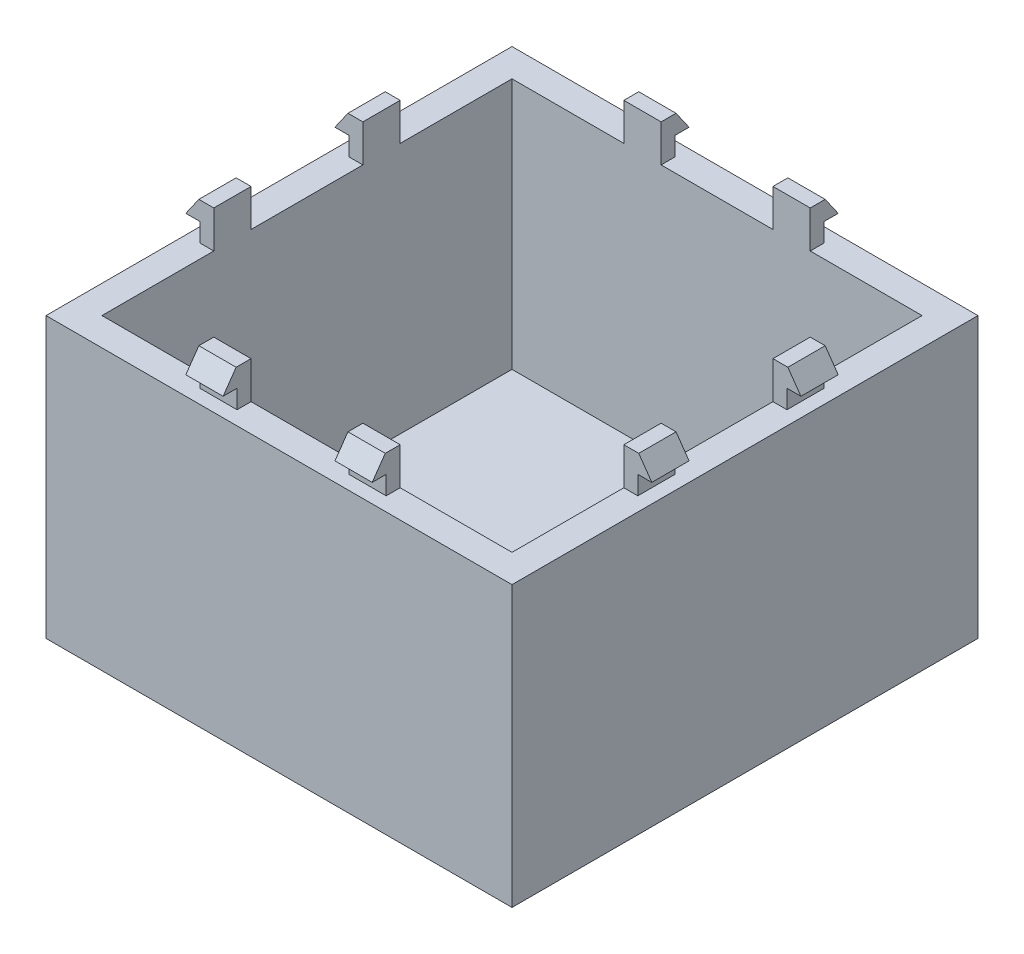
SolidWorks part; units mm, degrees
ref_plane "前视基准面" through (0, 0, 0) normal (0, 0, 1) x (1, 0, 0)
ref_plane "上视基准面" through (0, 0, 0) normal (0, 1, 0) x (1, 0, 0)
ref_plane "右视基准面" through (0, 0, 0) normal (1, 0, 0) x (0, 0, -1)
sketch "草图1" plane through (0, 0, 0) normal (0, 1, 0) x (1, 0, 0)
  line L1 (-25, 25) -> (25, 25)
  line L2 (-25, 25) -> (-25, -25)
  line L3 (-25, -25) -> (25, -25)
  line L4 (25, 25) -> (25, -25)
  line L5 (-25, 25) -> (25, -25) construction
  line L6 (-25, -25) -> (25, 25) construction
  point P0 (0, 0)
  dimension "D1" = 50
extrude "凸台-拉伸1" add sketch "草图1" along normal blind 3
sketch "草图2" plane through (0, 3, 0) normal (0, 1, 0) x (1, 0, 0)
  line L1 (-25, 25) -> (25, 25)
  line L2 (-25, 25) -> (-25, -25)
  line L3 (-25, -25) -> (25, -25)
  line L4 (25, 25) -> (25, -25)
  line L5 (-25, 25) -> (25, -25) construction
  line L6 (-25, -25) -> (25, 25) construction
  line L7 (-22, 22) -> (22, 22)
  line L8 (-22, 22) -> (-22, -22)
  line L9 (-22, -22) -> (22, -22)
  line L10 (22, 22) -> (22, -22)
  line L11 (-22, 22) -> (22, -22) construction
  line L12 (-22, -22) -> (22, 22) construction
  point P0 (0, 0)
  point P7 (0, 0)
  dimension "D1" = 44
extrude "凸台-拉伸2" add sketch "草图2" along normal blind 27
sketch "草图3" plane through (0, 30, 0) normal (0, 1, 0) x (1, 0, 0)
  line L0 (-22, -22) -> (22, -22) construction
  line L1 (-10, -22) -> (-6, -22)
  line L2 (-10, -22) -> (-10, -23.5)
  line L3 (-10, -23.5) -> (-6, -23.5)
  line L4 (-6, -22) -> (-6, -23.5)
  line L5 (0, 27.8778) -> (0, -48.568) construction
  line L6 (-22, 22) -> (-22, -22) construction
  line L7 (6, -22) -> (6, -23.5)
  line L8 (10, -23.5) -> (6, -23.5)
  line L9 (10, -22) -> (10, -23.5)
  line L10 (10, -22) -> (6, -22)
  line L12 (-22, 10) -> (-22, 6)
  line L13 (-22, 10) -> (-23.5, 10)
  line L14 (-23.5, 10) -> (-23.5, 6)
  line L15 (-22, 6) -> (-23.5, 6)
  line L16 (-22, -6) -> (-23.5, -6)
  line L17 (-23.5, -10) -> (-23.5, -6)
  line L18 (-22, -10) -> (-23.5, -10)
  line L19 (-22, -10) -> (-22, -6)
  line L20 (27.8778, 0) -> (-48.568, 0) construction
  line L21 (10, 22) -> (6, 22)
  line L22 (10, 22) -> (10, 23.5)
  line L23 (10, 23.5) -> (6, 23.5)
  line L24 (6, 22) -> (6, 23.5)
  line L25 (-6, 22) -> (-6, 23.5)
  line L26 (-10, 23.5) -> (-6, 23.5)
  line L27 (-10, 22) -> (-10, 23.5)
  line L28 (-10, 22) -> (-6, 22)
  line L29 (0, -27.8778) -> (0, 48.568) construction
  line L30 (22, -10) -> (22, -6)
  line L31 (22, -10) -> (23.5, -10)
  line L32 (23.5, -10) -> (23.5, -6)
  line L33 (22, -6) -> (23.5, -6)
  line L34 (22, 6) -> (23.5, 6)
  line L35 (23.5, 10) -> (23.5, 6)
  line L36 (22, 10) -> (23.5, 10)
  line L37 (22, 10) -> (22, 6)
  line L38 (-27.8778, 0) -> (48.568, 0) construction
  point P15 (0, 0)
  point P16 (0, 0)
  point P48 (0, 0)
  point P49 (0, 0)
  dimension "D1" = 12
  dimension "D2" = 4
  dimension "D3" = 1.5
  dimension "D4" = 4
extrude "凸台-拉伸3" add sketch "草图3" along normal blind 4
sketch "草图4" plane through (0, 34, 0) normal (0, 1, 0) x (1, 0, 0)
  line L0 (-23.5, 6) -> (-22, 6) construction
  line L1 (-23.5, 10) -> (-23.6, 10)
  line L2 (-23.5, 10) -> (-23.5, 6)
  line L3 (-23.5, 6) -> (-23.6, 6)
  line L4 (-23.6, 10) -> (-23.6, 6)
  dimension "D1" = 0.1
ref_plane "基准面1" through (0, 32, 0) normal (0, 1, 0) x (1, 0, 0)
sketch "草图6" plane through (0, 32, 0) normal (0, 1, 0) x (1, 0, 0)
  line L1 (-23.5, 10) -> (-25, 10)
  line L2 (-23.5, 10) -> (-23.5, 6)
  line L3 (-23.5, 6) -> (-25, 6)
  line L4 (-25, 10) -> (-25, 6)
  dimension "D1" = 1.5
sketch "草图8" plane through (0, 34, 0) normal (0, 1, 0) x (1, 0, 0)
  line L0 (-22, -6) -> (-23.5, -6) construction
  line L1 (-23.5, -6) -> (-23.6, -6)
  line L2 (-23.5, -6) -> (-23.5, -10)
  line L3 (-23.5, -10) -> (-23.6, -10)
  line L4 (-23.6, -6) -> (-23.6, -10)
  line L5 (-23.5, -6) -> (-23.5, -10) construction
  line L6 (-23.5, -10) -> (-22, -10) construction
  dimension "D1" = 0.1
sketch "草图9" plane through (0, 32, 0) normal (0, 1, 0) x (1, 0, 0)
  line L1 (-23.5, -6) -> (-25, -6)
  line L2 (-23.5, -6) -> (-23.5, -10)
  line L3 (-23.5, -10) -> (-25, -10)
  line L4 (-25, -6) -> (-25, -10)
  dimension "D1" = 1.5
loft "放样2" add profiles "草图4", "草图6"
loft "放样3" add profiles "草图8", "草图9"
sketch "草图10" plane through (0, 34, 0) normal (0, 1, 0) x (1, 0, 0)
  line L1 (-10, -23.5) -> (-6, -23.5)
  line L2 (-10, -23.5) -> (-10, -23.6)
  line L3 (-10, -23.6) -> (-6, -23.6)
  line L4 (-6, -23.5) -> (-6, -23.6)
  dimension "D1" = 0.1
sketch "草图11" plane through (0, 32, 0) normal (0, 1, 0) x (1, 0, 0)
  line L1 (-10, -23.5) -> (-6, -23.5)
  line L2 (-10, -23.5) -> (-10, -25)
  line L3 (-10, -25) -> (-6, -25)
  line L4 (-6, -23.5) -> (-6, -25)
  dimension "D1" = 1.5
sketch "草图12" plane through (0, 34, 0) normal (0, 1, 0) x (1, 0, 0)
  line L1 (6, -23.5) -> (10, -23.5)
  line L2 (6, -23.5) -> (6, -23.6)
  line L3 (6, -23.6) -> (10, -23.6)
  line L4 (10, -23.5) -> (10, -23.6)
  dimension "D1" = 0.1
sketch "草图13" plane through (0, 32, 0) normal (0, 1, 0) x (1, 0, 0)
  line L1 (6, -23.5) -> (10, -23.5)
  line L2 (6, -23.5) -> (6, -25)
  line L3 (6, -25) -> (10, -25)
  line L4 (10, -23.5) -> (10, -25)
  dimension "D1" = 1.5
loft "放样4" add profiles "草图10", "草图11"
loft "放样5" add profiles "草图12", "草图13"
sketch "草图14" plane through (0, 34, 0) normal (0, 1, 0) x (1, 0, 0)
  line L1 (23.5, -10) -> (23.6, -10)
  line L2 (23.5, -10) -> (23.5, -6)
  line L3 (23.5, -6) -> (23.6, -6)
  line L4 (23.6, -10) -> (23.6, -6)
  dimension "D1" = 0.1
sketch "草图15" plane through (0, 32, 0) normal (0, 1, 0) x (1, 0, 0)
  line L1 (23.5, -10) -> (25, -10)
  line L2 (23.5, -10) -> (23.5, -6)
  line L3 (23.5, -6) -> (25, -6)
  line L4 (25, -10) -> (25, -6)
  dimension "D1" = 1.5
sketch "草图16" plane through (0, 34, 0) normal (0, 1, 0) x (1, 0, 0)
  line L1 (23.5, 6) -> (23.6, 6)
  line L2 (23.5, 6) -> (23.5, 10)
  line L3 (23.5, 10) -> (23.6, 10)
  line L4 (23.6, 6) -> (23.6, 10)
  dimension "D1" = 0.1
sketch "草图17" plane through (0, 32, 0) normal (0, 1, 0) x (1, 0, 0)
  line L1 (23.5, 6) -> (25, 6)
  line L2 (23.5, 6) -> (23.5, 10)
  line L3 (23.5, 10) -> (25, 10)
  line L4 (25, 6) -> (25, 10)
  dimension "D1" = 1.5
loft "放样6" add profiles "草图14", "草图15"
loft "放样7" add profiles "草图16", "草图17"
sketch "草图18" plane through (0, 34, 0) normal (0, 1, 0) x (1, 0, 0)
  line L1 (-6, 23.5) -> (-10, 23.5)
  line L2 (-6, 23.5) -> (-6, 23.6)
  line L3 (-6, 23.6) -> (-10, 23.6)
  line L4 (-10, 23.5) -> (-10, 23.6)
  dimension "D1" = 0.1
sketch "草图19" plane through (0, 32, 0) normal (0, 1, 0) x (1, 0, 0)
  line L1 (-6, 23.5) -> (-10, 23.5)
  line L2 (-6, 23.5) -> (-6, 25)
  line L3 (-6, 25) -> (-10, 25)
  line L4 (-10, 23.5) -> (-10, 25)
  dimension "D1" = 1.5
sketch "草图20" plane through (0, 34, 0) normal (0, 1, 0) x (1, 0, 0)
  line L0 (10, 23.5) -> (6, 23.5) construction
  line L1 (10, 23.5) -> (6, 23.5)
  line L2 (10, 23.5) -> (10, 23.6)
  line L3 (10, 23.6) -> (6, 23.6)
  line L4 (6, 23.5) -> (6, 23.6)
  dimension "D1" = 0.1
sketch "草图21" plane through (0, 32, 0) normal (0, 1, 0) x (1, 0, 0)
  line L1 (10, 23.5) -> (6, 23.5)
  line L2 (10, 23.5) -> (10, 25)
  line L3 (10, 25) -> (6, 25)
  line L4 (6, 23.5) -> (6, 25)
  dimension "D1" = 1.5
loft "放样8" add profiles "草图18", "草图19"
loft "放样9" add profiles "草图20", "草图21"
